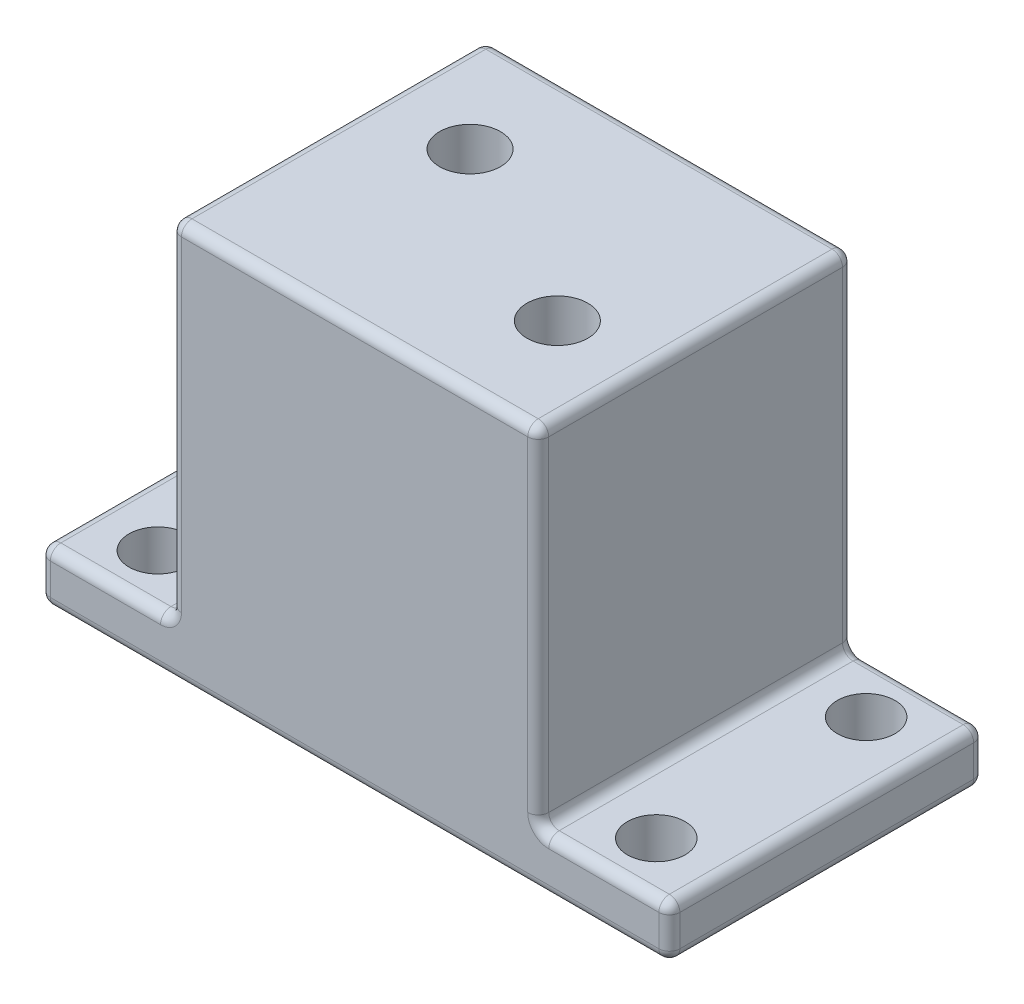
SolidWorks part; units mm, degrees
ref_plane "Front Plane" through (0, 0, 0) normal (0, 0, 1) x (1, 0, 0)
ref_plane "Top Plane" through (0, 0, 0) normal (0, 1, 0) x (1, 0, 0)
ref_plane "Right Plane" through (0, 0, 0) normal (1, 0, 0) x (0, 0, -1)
sketch "Sketch2" plane through (0, 0, 0) normal (0, 1, 0) x (1, 0, 0)
  line L1 (60, 0) -> (0, 0)
  line L2 (60, 0) -> (60, -30)
  line L3 (60, -30) -> (0, -30)
  line L4 (0, 0) -> (0, -30)
  dimension "D1" = 60
  dimension "D2" = 30
extrude "Boss-Extrude1" add sketch "Sketch2" along normal blind 5
sketch "Sketch3" plane through (0, 5, 0) normal (0, 1, 0) x (1, 0, 0)
  line L0 (60, -30) -> (0, 0) construction
  line L1 (60, 0) -> (0, 0) construction
  line L2 (12.5, -30) -> (47.5, -30)
  line L3 (12.5, -30) -> (12.5, 0)
  line L4 (12.5, 0) -> (47.5, 0)
  line L5 (47.5, -30) -> (47.5, 0)
  line L6 (12.5, -30) -> (47.5, 0) construction
  line L7 (12.5, 0) -> (47.5, -30) construction
  point P4 (30, -15)
  dimension "D1" = 35
extrude "Boss-Extrude2" add sketch "Sketch3" along normal blind 33
sketch "Sketch5" plane through (0, 38, 0) normal (0, 1, 0) x (1, 0, 0)
  line L0 (39.325, 0) -> (39.325, -20) construction
  line L1 (47.5, 0) -> (12.5, 0) construction
  line L2 (21, -10) -> (0, -10) construction
  line L3 (0, 0) -> (0, -30) construction
  line L4 (39.325, -20) -> (0, -20) construction
  line L5 (21, -10) -> (21, 0) construction
  circle A0 centre (21, -10) radius 2.9
  circle A1 centre (39.325, -20) radius 2.9
  dimension "D5" = 5.8
  dimension "D1" = 21
  dimension "D2" = 10
  dimension "D3" = 20
  dimension "D4" = 39.325
extrude "Cut-Extrude1" cut sketch "Sketch5" against normal blind 20
sketch "Sketch6" plane through (0, 5, 0) normal (0, 1, 0) x (1, 0, 0)
  line L0 (6.25, 0) -> (6.25, -5) construction
  line L3 (12.5, 0) -> (0, 0) construction
  line L6 (6.25, -5) -> (6.25, -25) construction
  line L7 (6.25, -25) -> (6.25, -30) construction
  line L8 (0, -30) -> (12.5, -30) construction
  line L9 (53.75, -30) -> (53.75, -25) construction
  line L10 (47.5, -30) -> (60, -30) construction
  line L11 (53.75, -25) -> (53.75, -5) construction
  line L12 (53.75, -5) -> (53.75, 0) construction
  line L13 (60, 0) -> (47.5, 0) construction
  circle A0 centre (53.75, -5) radius 2.75
  circle A1 centre (53.75, -25) radius 2.75
  circle A2 centre (6.25, -25) radius 2.75
  circle A3 centre (6.25, -5) radius 2.75
  dimension "D2" = 5.5
  dimension "D1" = 5
extrude "Cut-Extrude2" cut sketch "Sketch6" against normal through all
fillet "Fillet1" radius 1 24 edges at (0, 5, 15) (0, 0, 15) (60, 5, 15) (60, 0, 15) (47.5, 38, 15) (47.5, 5, 15) (12.5, 38, 15) (12.5, 5, 15) (60, 2.5, 0) (53.75, 5, 0) (47.5, 21.5, 0) (30, 38, 0) (12.5, 21.5, 0) (6.25, 5, 0) (0, 2.5, 0) (30, 0, 0) (0, 2.5, 30) (6.25, 5, 30) (12.5, 21.5, 30) (30, 38, 30) (47.5, 21.5, 30) (53.75, 5, 30) (60, 2.5, 30) (30, 0, 30)
